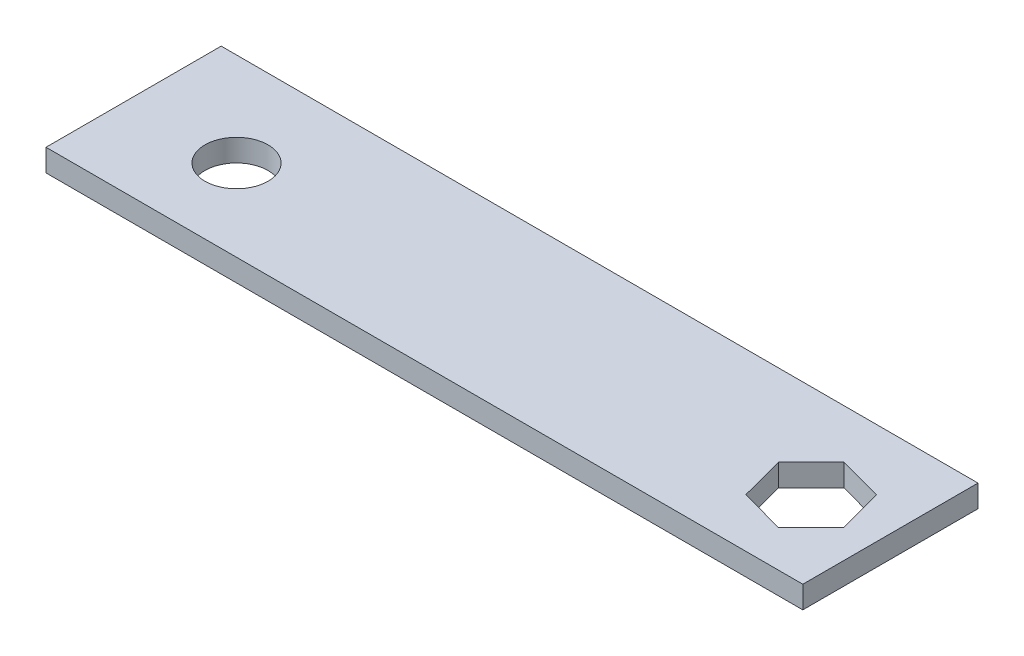
SolidWorks part; units mm, degrees
ref_plane "Front" through (0, 0, 0) normal (0, 0, 1) x (1, 0, 0)
ref_plane "Top" through (0, 0, 0) normal (0, 1, 0) x (1, 0, 0)
ref_plane "Right" through (0, 0, 0) normal (1, 0, 0) x (0, 0, -1)
sketch "Sketch1" plane through (0, 0, 0) normal (0, 1, 0) x (1, 0, 0)
  line L1 (0, 0) -> (108, 0)
  line L2 (0, 0) -> (0, 25)
  line L3 (0, 25) -> (108, 25)
  line L4 (108, 0) -> (108, 25)
  line L5 (95.8519, 18.017) -> (91.1786, 13.3668)
  line L6 (91.1786, 13.3668) -> (92.8692, 6.9945)
  line L7 (92.8692, 6.9945) -> (99.233, 5.2724)
  line L8 (99.233, 5.2724) -> (103.9063, 9.9226)
  line L9 (103.9063, 9.9226) -> (102.2157, 16.2949)
  line L10 (102.2157, 16.2949) -> (95.8519, 18.017)
  circle A1 centre (15.5424, 11.6447) radius 4.5
  circle A2 centre (97.5424, 11.6447) radius 5.7095 construction
  dimension "D1" = 108
  dimension "D2" = 25
extrude "Boss-Extrude1" add sketch "Sketch1" along normal blind 3.175
